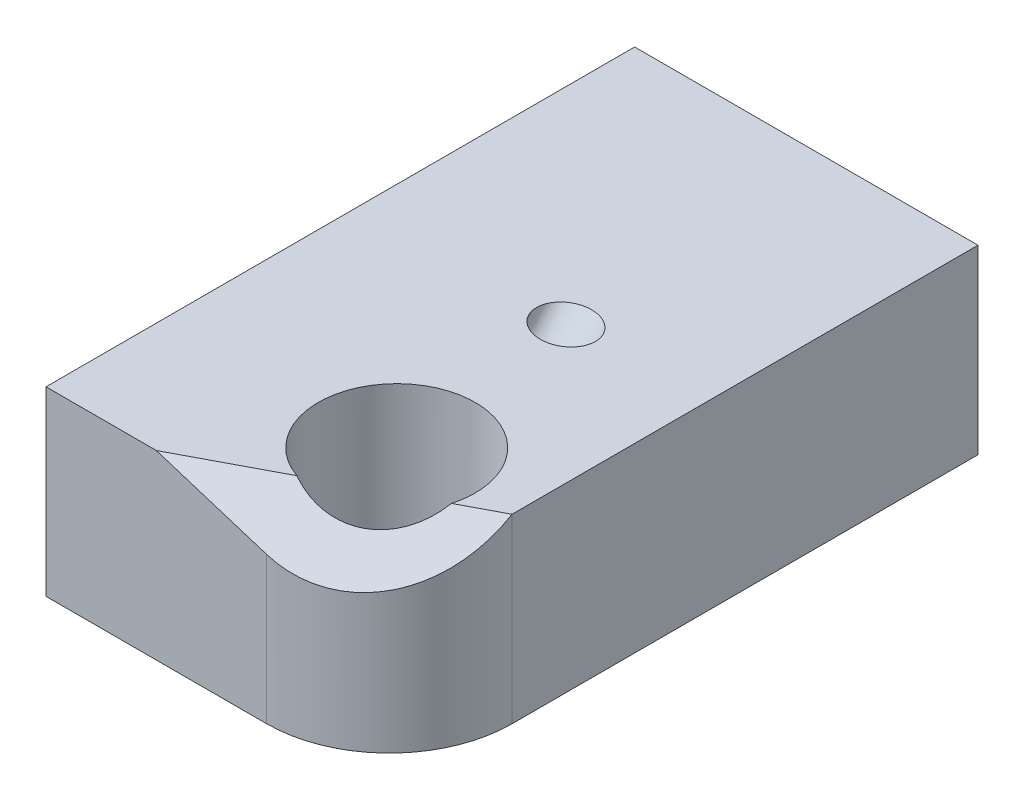
SolidWorks part; units mm, degrees
ref_plane "Front Plane" through (0, 0, 0) normal (0, 0, 1) x (1, 0, 0)
ref_plane "Top Plane" through (0, 0, 0) normal (0, 1, 0) x (1, 0, 0)
ref_plane "Right Plane" through (0, 0, 0) normal (1, 0, 0) x (0, 0, -1)
sketch "Sketch1" plane through (0, 0, 0) normal (0, 1, 0) x (1, 0, 0)
  line L1 (-44.45, -76.2) -> (44.45, -76.2)
  line L2 (-44.45, -76.2) -> (-44.45, 76.2)
  line L3 (-44.45, 76.2) -> (44.45, 76.2)
  line L4 (44.45, -76.2) -> (44.45, 76.2)
  line L5 (-44.45, -76.2) -> (44.45, 76.2) construction
  line L6 (-44.45, 76.2) -> (44.45, -76.2) construction
  point P0 (0, 0)
  dimension "D1" = 152.4
  dimension "D2" = 88.9
extrude "Boss-Extrude1" add sketch "Sketch1" along normal blind 46.99
fillet "Fillet1" radius 31.75 1 edges at (44.45, 23.495, 76.2)
sketch "Sketch6" plane through (0, 46.99, 0) normal (0, 1, 0) x (1, 0, 0)
  line L0 (-44.45, -76.2) -> (12.7, -76.2) construction
  circle A0 centre (14.605, -44.45) radius 20.32
  point P5 (0, 0)
  point P6 (0, 0)
  point P7 (-15.875, -76.2)
  dimension "D2" = 40.64
  dimension "D1" = 30.48
sketch "Sketch8" plane through (0, 0, 76.2) normal (0, 0, 1) x (1, 0, 0)
  line L0 (44.45, 46.99) -> (44.45, 0) construction
  line L1 (-44.45, 46.99) -> (12.7, 46.99) construction
  point P0 (44.45, 27.94)
  dimension "D1" = 19.05
sketch "Sketch9" plane through (0, 46.99, 0) normal (0, 1, 0) x (1, 0, 0)
  point P0 (44.45, -44.45)
ref_plane "Plane1" through (18.9719, 60.0777, 36.0466) normal (0.2614, 0.8277, 0.4966) x (0.9652, -0.2241, -0.1345)
sketch "Sketch11" plane through (18.9719, 60.0777, 36.0466) normal (0.2614, 0.8277, 0.4966) x (0.9652, -0.2241, -0.1345)
  line L0 (-36.1019, -41.1648) -> (26.3957, -50.9659)
  line L1 (-63.6836, -41.1648) -> (-8.5202, -41.1648) construction
  line L2 (26.3957, -50.9659) -> (26.3957, -13.9394)
  line L3 (26.3957, -13.9394) -> (-36.1019, -41.1648)
extrude "Cut-Extrude1" cut sketch "Sketch11" along normal through all
extrude "Cut-Extrude2" cut sketch "Sketch6" against normal blind 40.64 contours A0
sketch "Sketch12" plane through (0, 46.99, 0) normal (0, 1, 0) x (1, 0, 0)
  line L0 (44.45, 76.2) -> (-44.45, 76.2) construction
  line L1 (44.45, -44.45) -> (44.45, 76.2) construction
  point P0 (8.89, 5.08)
  dimension "D1" = 71.12
  dimension "D2" = 35.56
ref_plane "Plane4" through (0, 65.096, -54.6221) normal (0, 0.766, -0.6428) x (-1, 0, 0)
sketch "Sketch14" plane through (0, 65.096, -54.6221) normal (0, 0.766, -0.6428) x (-1, 0, 0)
  ellipse E0 centre (-8.89, 26.3131) end of major axis (-16.51, 26.3131) minor radius 5.08
  point P1 (-8.89, 39.0426)
  point P7 (0, 0)
  point P9 (0, 0)
  dimension "D1" = 7.62
  dimension "D2" = 10.16
extrude "Cut-Extrude3" cut sketch "Sketch14" against normal up to surface (91.297 mm away) contours E0
